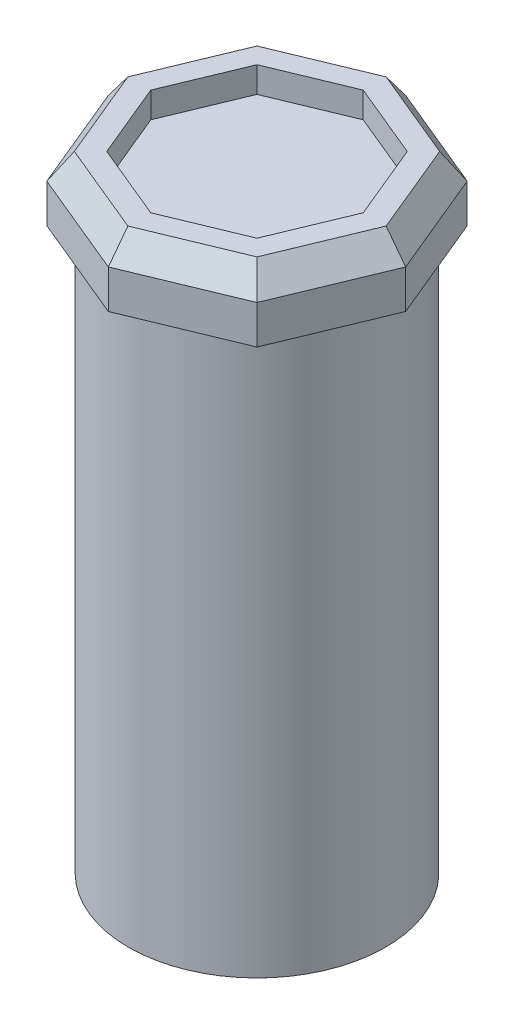
SolidWorks part; units mm, degrees
material "1060 Alloy"
ref_plane "Front Plane" through (0, 0, 0) normal (0, 0, 1) x (1, 0, 0)
ref_plane "Top Plane" through (0, 0, 0) normal (0, 1, 0) x (1, 0, 0)
ref_plane "Right Plane" through (0, 0, 0) normal (1, 0, 0) x (0, 0, -1)
sketch "Sketch1" plane through (0, 0, 0) normal (0, 1, 0) x (1, 0, 0)
  circle A0 centre (0, 0) radius 12.7
  dimension "D1" = 25.4
extrude "Boss-Extrude1" add sketch "Sketch1" along normal blind 57.15
sketch "Sketch2" plane through (0, 57.15, 0) normal (0, 1, 0) x (1, 0, 0)
  line L1 (0, 14.6814) -> (-10.3813, 10.3813)
  line L2 (-10.3813, 10.3813) -> (-14.6814, 0)
  line L3 (-14.6814, 0) -> (-10.3813, -10.3813)
  line L4 (-10.3813, -10.3813) -> (0, -14.6814)
  line L5 (0, -14.6814) -> (10.3813, -10.3813)
  line L6 (10.3813, -10.3813) -> (14.6814, 0)
  line L7 (14.6814, 0) -> (10.3813, 10.3813)
  line L8 (10.3813, 10.3813) -> (0, 14.6814)
  circle A0 centre (0, 0) radius 13.5639 construction
extrude "Boss-Extrude2" add sketch "Sketch2" along normal blind 6.35
chamfer "Chamfer1" distance 2.54 angle 35 8 edges at (12.5314, 63.5, -5.1907) (12.5314, 63.5, 5.1907) (5.1907, 63.5, 12.5314) (-5.1907, 63.5, 12.5314) (-12.5314, 63.5, 5.1907) (-12.5314, 63.5, -5.1907) (-5.1907, 63.5, -12.5314) (5.1907, 63.5, -12.5314)
sketch "Sketch3" plane through (0, 63.5, 0) normal (0, 1, 0) x (1, 0, 0)
  line L1 (0, 10.4931) -> (-7.4197, 7.4197)
  line L2 (-7.4197, 7.4197) -> (-10.4931, 0)
  line L3 (-10.4931, 0) -> (-7.4197, -7.4197)
  line L4 (-7.4197, -7.4197) -> (0, -10.4931)
  line L5 (0, -10.4931) -> (7.4197, -7.4197)
  line L6 (7.4197, -7.4197) -> (10.4931, 0)
  line L7 (10.4931, 0) -> (7.4197, 7.4197)
  line L8 (7.4197, 7.4197) -> (0, 10.4931)
  circle A0 centre (0, 0) radius 9.6944 construction
extrude "Cut-Extrude1" cut sketch "Sketch3" against normal blind 2.54
chamfer "Chamfer2" distance 2.54 angle 35 1 edges at (0, 0, 12.7)
